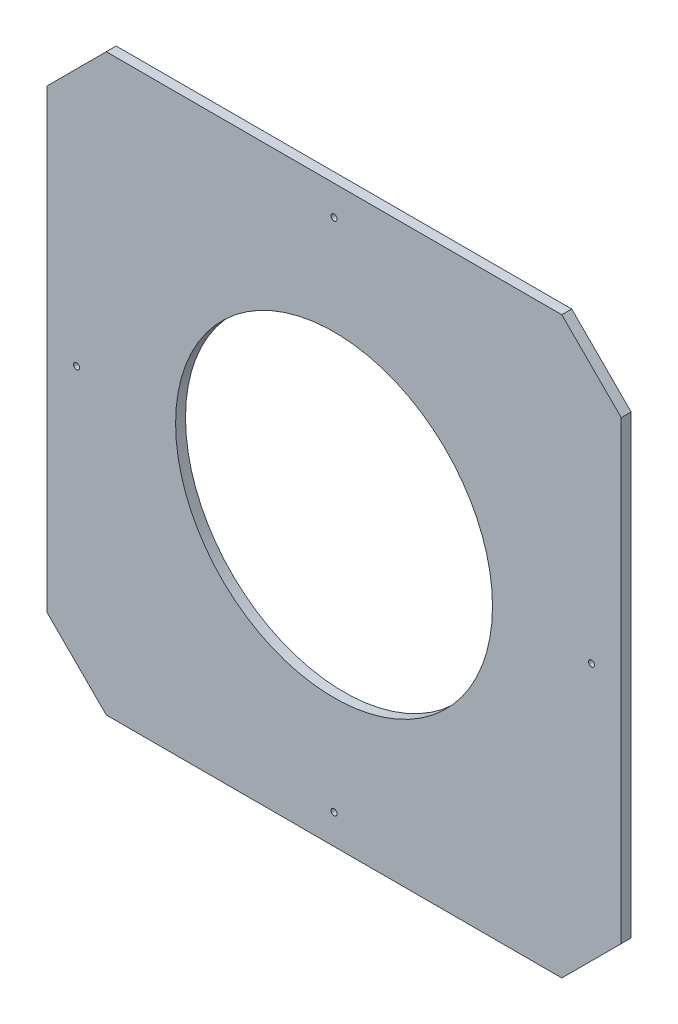
SolidWorks part; units mm, degrees
ref_plane "Front Plane" through (0, 0, 0) normal (0, 0, 1) x (1, 0, 0)
ref_plane "Top Plane" through (0, 0, 0) normal (0, 1, 0) x (1, 0, 0)
ref_plane "Right Plane" through (0, 0, 0) normal (1, 0, 0) x (0, 0, -1)
sketch "Sketch1" plane through (0, 0, 0) normal (0, 0, 1) x (1, 0, 0)
  line L0 (115, 145) -> (145, 115)
  line L1 (-120, 150) -> (120, 150)
  line L2 (-150, 120) -> (-150, -120)
  line L3 (-120, -150) -> (120, -150)
  line L4 (150, 120) -> (150, -120)
  line L5 (-150, 150) -> (150, -150) construction
  line L6 (-150, -150) -> (150, 150) construction
  line L7 (-115, 145) -> (115, 145)
  line L8 (-145, 115) -> (-145, -115)
  line L9 (-115, -145) -> (115, -145)
  line L10 (145, 115) -> (145, -115)
  line L11 (-145, 145) -> (145, -145) construction
  line L12 (-145, -145) -> (145, 145) construction
  line L13 (120, 150) -> (150, 120)
  line L14 (115, -145) -> (145, -115)
  line L15 (150, -120) -> (120, -150)
  line L16 (-145, -115) -> (-115, -145)
  line L17 (-150, -120) -> (-120, -150)
  line L18 (-145, 115) -> (-115, 145)
  line L19 (-150, 120) -> (-120, 150)
  circle A0 centre (0, 0) radius 80
  point P1 (0, 0)
  point P7 (0, 0)
  dimension "D4" = 160
  dimension "D1" = 290
  dimension "D3" = 300
extrude "Boss-Extrude1" add sketch "Sketch1" along normal blind 5 contours L18 L8 L16 L9 L14 L10 L0 L7 A0
sketch "Sketch3" plane through (0, 0, 0) normal (0, 0, 1) x (1, 0, 0)
  point P0 (0, 130)
  point P15 (130, 0)
  point P16 (0, -130)
  point P17 (-130, 0)
  dimension "D1" = 4
hole_wizard "Ø3.0mm Dowel Hole1" positions "Sketch4" profile "Sketch5" hole size "Ø3.0" standard "ISO"
sketch "Sketch4" plane through (0, 0, 5) normal (0, 0, 1) x (1, 0, 0)
  point P0 (0, 130)
  point P3 (130, 0)
  point P6 (0, -130)
  point P9 (-130, 0)
sketch "Sketch5" plane through (0, 130, 5) normal (1, 0, 0) x (0, -1, 0)
  line L0 (0, 0) -> (0, 8.4013)
  line L1 (0, 8.4013) -> (1.5, 7.5)
  line L2 (1.5, 7.5) -> (1.5, 0.025)
  line L3 (1.5, 0.025) -> (1.525, 0)
  line L5 (1.525, 0) -> (0, 0)
  line L6 (-1.5, 0.025) -> (-1.525, 0) construction
  line L10 (0, 8.4013) -> (-1.5, 7.5) construction
  line L11 (0, -6.35) -> (0, 107.95) construction
  dimension "Hole Dia." = 3
  dimension "Hole Depth" = 7.5
  dimension "Near C'Sink Dia." = 3.05
  dimension "Near C'Sink Angle" = 90
  dimension "Drill Angle" = 118
